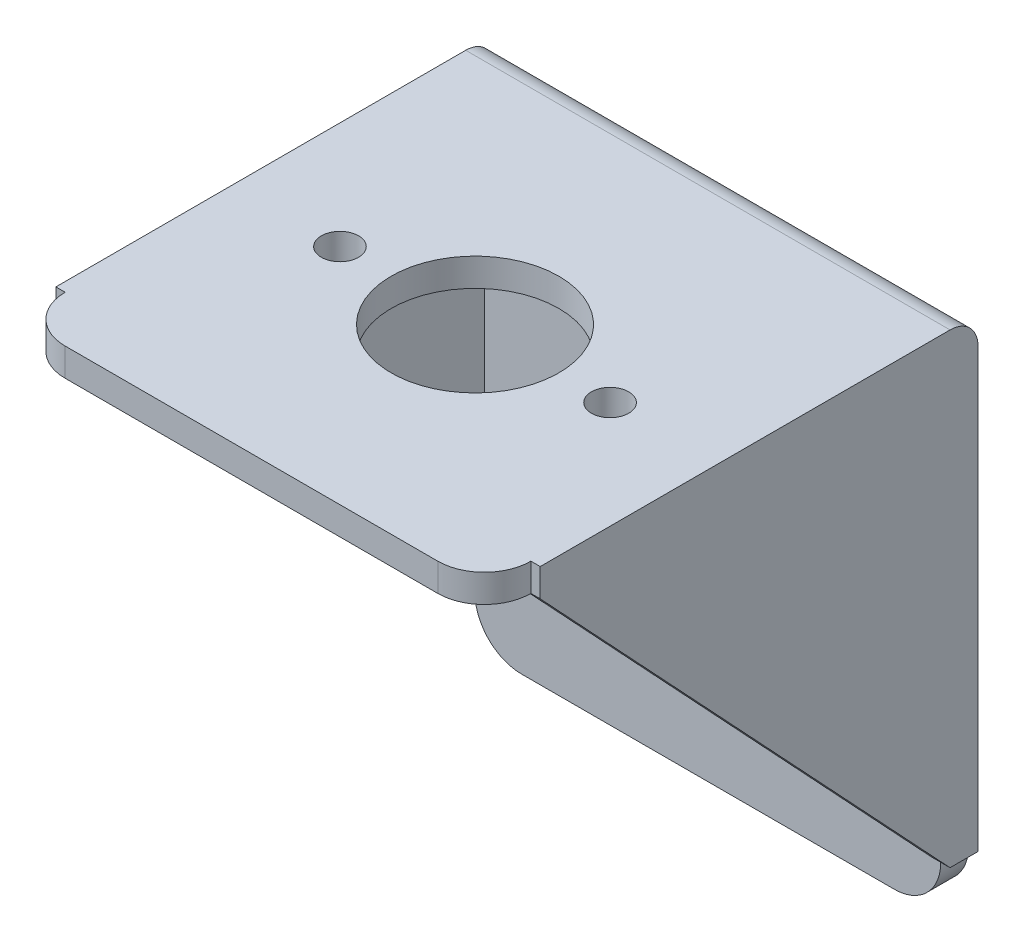
SolidWorks part; units mm, degrees
ref_plane "Front Plane" through (0, 0, 0) normal (0, 0, 1) x (1, 0, 0)
ref_plane "Top Plane" through (0, 0, 0) normal (0, 1, 0) x (1, 0, 0)
ref_plane "Right Plane" through (0, 0, 0) normal (1, 0, 0) x (0, 0, -1)
ref_plane "Plane1" through (50, 0, 0) normal (1, 0, 0) x (0, 0, -1)
sketch "Sketch1" plane through (50, 0, 0) normal (1, 0, 0) x (0, 0, -1)
  line L0 (0, -52) -> (0, 3)
  line L1 (0, 3) -> (-52, 3)
  line L2 (-52, 3) -> (-52, -52)
  line L3 (-52, -52) -> (0, -52)
extrude "Boss-Extrude1" add sketch "Sketch1" against normal blind 50
sketch "Sketch2" plane through (0, 0, 0) normal (-1, 0, 0) x (0, 0, 1)
  line L0 (3, 0) -> (3, -52)
  line L1 (3, -52) -> (52, -52)
  line L2 (52, -52) -> (52, 0)
  line L3 (52, 0) -> (3, 0)
extrude "Cut-Extrude1" cut sketch "Sketch2" against normal through all
sketch "Sketch3" plane through (0, 0, 0) normal (0, 0, -1) x (-1, 0, 0)
  line L0 (-33.1, -37.9) -> (-38.9, -37.9)
  line L1 (-38.9, -42.1) -> (-33.1, -42.1)
  arc A0 (-38.9, -37.9) -> (-38.9, -42.1) centre (-38.9, -40) ccw
  arc A1 (-33.1, -42.1) -> (-33.1, -37.9) centre (-33.1, -40) ccw
extrude "Cut-Extrude2" cut sketch "Sketch3" against normal through all
sketch "Sketch4" plane through (0, 0, 0) normal (0, 0, -1) x (-1, 0, 0)
  line L0 (-16.9, -14.1) -> (-11.1, -14.1)
  line L1 (-11.1, -9.9) -> (-16.9, -9.9)
  arc A0 (-11.1, -14.1) -> (-11.1, -9.9) centre (-11.1, -12) ccw
  arc A1 (-16.9, -9.9) -> (-16.9, -14.1) centre (-16.9, -12) ccw
extrude "Cut-Extrude3" cut sketch "Sketch4" against normal through all
sketch "Sketch5" plane through (0, 0, 0) normal (0, 0, -1) x (-1, 0, 0)
  line L0 (-16.9, -42.1) -> (-11.1, -42.1)
  line L1 (-11.1, -37.9) -> (-16.9, -37.9)
  arc A0 (-11.1, -42.1) -> (-11.1, -37.9) centre (-11.1, -40) ccw
  arc A1 (-16.9, -37.9) -> (-16.9, -42.1) centre (-16.9, -40) ccw
extrude "Cut-Extrude4" cut sketch "Sketch5" against normal through all
sketch "Sketch6" plane through (0, 0, 3) normal (0, 0, 1) x (1, 0, 0)
  line L0 (38.9, -9.9) -> (33.1, -9.9)
  line L1 (33.1, -14.1) -> (38.9, -14.1)
  arc A0 (38.9, -14.1) -> (38.9, -9.9) centre (38.9, -12) ccw
  arc A1 (33.1, -9.9) -> (33.1, -14.1) centre (33.1, -12) ccw
extrude "Cut-Extrude5" cut sketch "Sketch6" against normal through all
hole_wizard "Ø18.0 (18) Diameter Hole1" positions "Sketch8" profile "Sketch7" hole size "Ø18.0" standard "ANSI Metric"
sketch "Sketch8" plane through (0, 0, 0) normal (0, -1, 0) x (-1, 0, 0)
  point P0 (-25, -28)
sketch "Sketch7" plane through (25, 0, 28) normal (1, 0, 0) x (0, 0, -1)
  line L0 (0, 0) -> (0, 3)
  line L1 (0, 3) -> (9, 3)
  line L2 (9, 3) -> (9, 0)
  line L5 (9, 0) -> (0, 0)
  line L11 (0, -6.35) -> (0, 107.95) construction
  dimension "Thru Hole Dia." = 18
  dimension "Thru Hole Depth" = 3
hole_wizard "Ø4.0 (4) Diameter Hole1" positions "Sketch10" profile "Sketch9" hole size "Ø4.0" standard "ANSI Metric"
sketch "Sketch10" plane through (0, 0, 0) normal (0, -1, 0) x (-1, 0, 0)
  point P0 (-10.5, -28)
  point P1 (-39.5, -28)
sketch "Sketch9" plane through (10.5, 0, 28) normal (1, 0, 0) x (0, 0, -1)
  line L0 (0, 0) -> (0, 3)
  line L1 (0, 3) -> (2, 3)
  line L2 (2, 3) -> (2, 0)
  line L5 (2, 0) -> (0, 0)
  line L11 (0, -6.35) -> (0, 107.95) construction
  dimension "Thru Hole Dia." = 4
  dimension "Thru Hole Depth" = 3
fillet "Fillet1" radius 3 1 edges at (25, 3, 0)
fillet "Fillet2" radius 5 4 edges at (50, 1.5, 52) (0, -52, 1.5) (50, -52, 1.5) (0, 1.5, 52)
sketch "Sketch12" plane through (0, 0, 0) normal (-1, 0, 0) x (0, 0, 1)
  line L0 (3, 0) -> (3, -47) construction
  line L1 (47, 0) -> (3, 0) construction
  line L2 (3, 0) -> (3, -47)
  line L3 (47, 0) -> (3, 0)
  line L4 (3, -47) -> (47, 0)
  line L5 (3, 0) -> (48.9069, 0)
  line L6 (3, 0) -> (3, -47)
  line M3 (3, -47) -> (3, 0)
  line M4 (3, 0) -> (47, 0)
extrude "Boss-Extrude2" add sketch "Sketch12" against normal blind 1 contours L4 M3 M4
sketch "Sketch13" plane through (50, 0, 0) normal (1, 0, 0) x (0, 0, -1)
  line L3 (-3, -47) -> (-3, 0)
  line L4 (-3, 0) -> (-47, 0)
  line L5 (-47, 0) -> (-3, -47)
  line L6 (-3, -47) -> (-3, 0)
  line L7 (-3, 0) -> (-47, 0)
  line L8 (-47, 0) -> (-3, -47)
  dimension "D1" = 0
extrude "Boss-Extrude3" add sketch "Sketch13" against normal blind 1
sketch "Sketch14" plane through (0, 0, 0) normal (-1, 0, 0) x (0, 0, 1)
  line L5 (0, 0) -> (0, -47)
  line L6 (0, -47) -> (3, -47)
  line L7 (3, -47) -> (47, 0)
  line L8 (47, 0) -> (47, 3)
  line L9 (47, 3) -> (3, 3)
  line L10 (0, 0) -> (0, -47)
  line L11 (0, -47) -> (3, -47)
  line L12 (3, -47) -> (47, 0)
  line L13 (47, 0) -> (47, 3)
  line L14 (47, 3) -> (3, 3)
  arc A1 (3, 3) -> (0, 0) centre (3, 0) ccw
  arc A2 (3, 3) -> (0, 0) centre (3, 0) ccw
  dimension "D1" = 0
extrude "Boss-Extrude4" add sketch "Sketch14" along normal blind 1
sketch "Sketch15" plane through (50, 0, 0) normal (1, 0, 0) x (0, 0, -1)
  line L5 (-3, 3) -> (-47, 3)
  line L6 (-47, 3) -> (-47, 0)
  line L7 (-47, 0) -> (-3, -47)
  line L8 (-3, -47) -> (0, -47)
  line L9 (0, -47) -> (0, 0)
  line L10 (-3, 3) -> (-47, 3)
  line L11 (-47, 3) -> (-47, 0)
  line L12 (-47, 0) -> (-3, -47)
  line L13 (-3, -47) -> (0, -47)
  line L14 (0, -47) -> (0, 0)
  arc A1 (0, 0) -> (-3, 3) centre (-3, 0) ccw
  arc A2 (0, 0) -> (-3, 3) centre (-3, 0) ccw
  dimension "D1" = 0
extrude "Boss-Extrude5" add sketch "Sketch15" along normal blind 1
